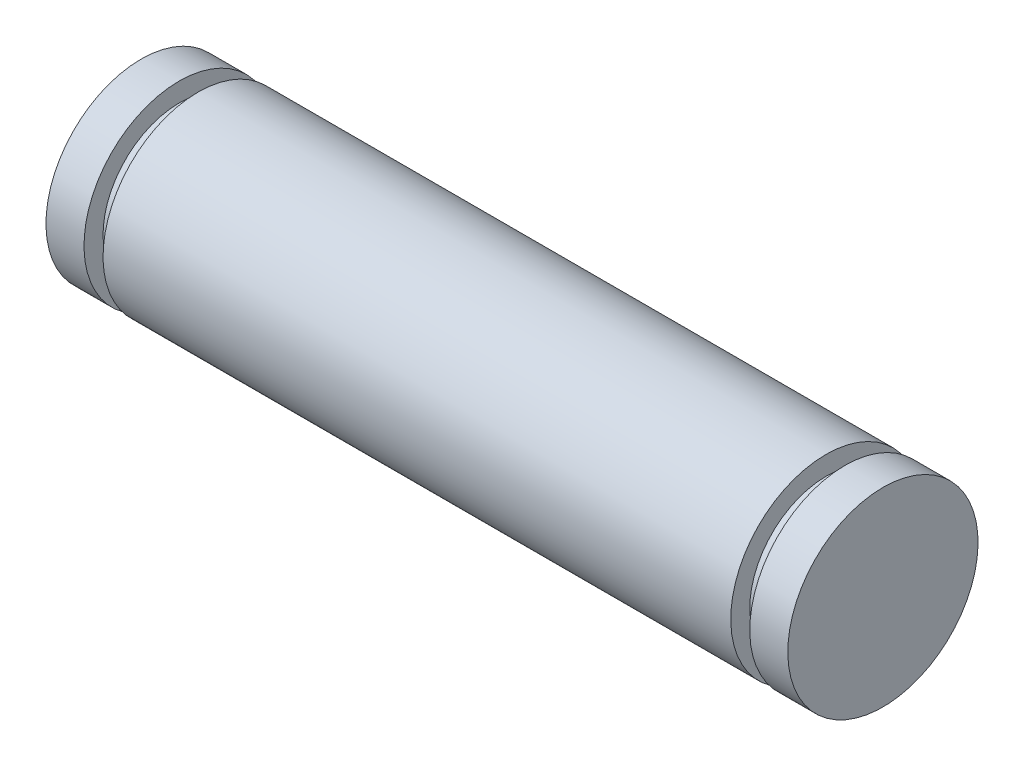
SolidWorks part; units mm, degrees
ref_plane "Front Plane" through (0, 0, 0) normal (0, 0, 1) x (1, 0, 0)
ref_plane "Top Plane" through (0, 0, 0) normal (0, 1, 0) x (1, 0, 0)
ref_plane "Right Plane" through (0, 0, 0) normal (1, 0, 0) x (0, 0, -1)
sketch "Sketch2" plane through (0, 0, 0) normal (0, 0, 1) x (1, 0, 0)
  line L0 (0, 0) -> (-19.5, 0) construction
  line L1 (0, 2.5) -> (0, 0)
  line L2 (-19.5, 2.5) -> (-18.5, 2.5)
  line L3 (-18.5, 2.5) -> (-18.5, 2)
  line L4 (-18.5, 2) -> (-18, 2)
  line L5 (-18, 2) -> (-18, 2.5)
  line L6 (-18, 2.5) -> (-1.5, 2.5)
  line L7 (-1.5, 2.5) -> (-1.5, 2)
  line L8 (-1.5, 2) -> (-1, 2)
  line L9 (-1, 2) -> (-1, 2.5)
  line L11 (0, 0) -> (-19.5, 0)
  line L12 (-19.5, 0) -> (-19.5, 2.5)
  line L13 (-1, 2.5) -> (0, 2.5)
  dimension "D1" = 2.5
  dimension "D2" = 19.5
  dimension "D3" = 1
  dimension "D4" = 0.5
  dimension "D5" = 16.5
  dimension "D6" = 0.5
revolve "Revolve1" add sketch "Sketch2" angle 360 about L11
